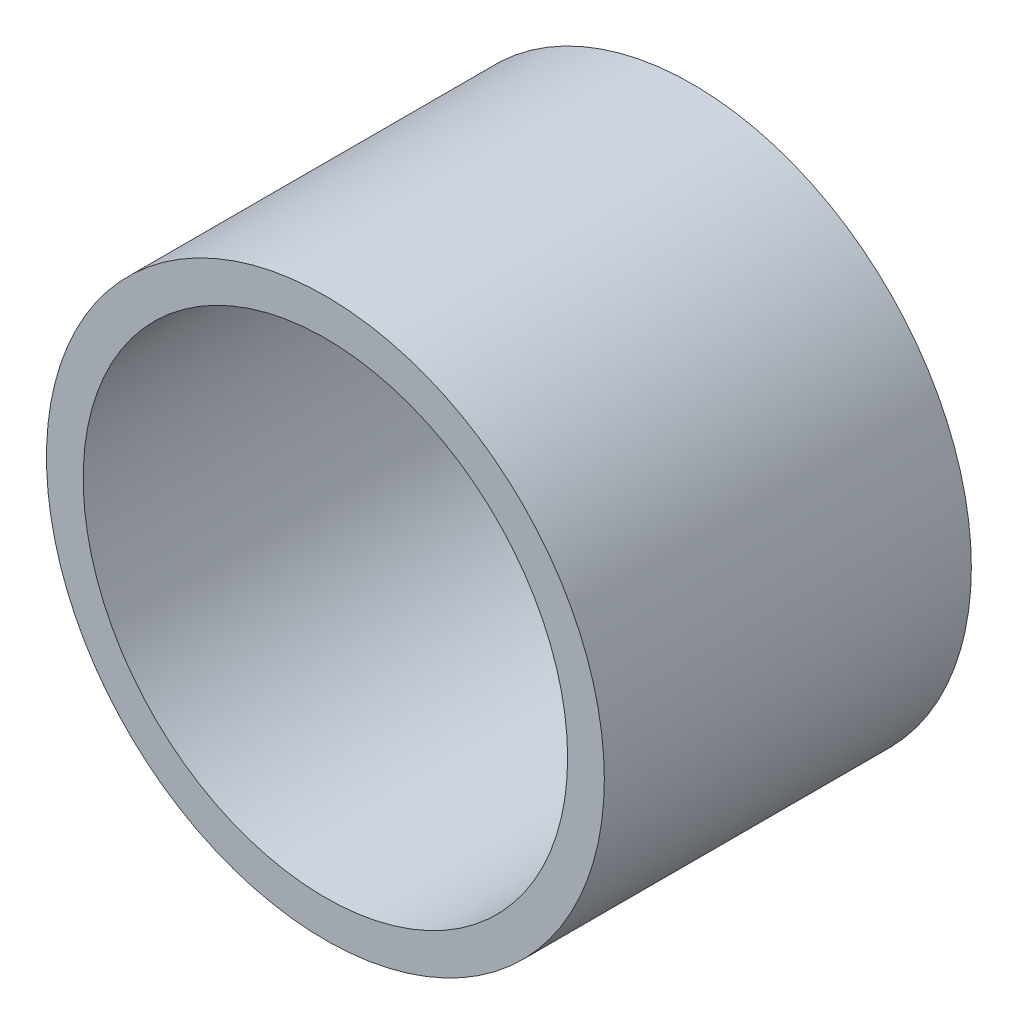
SolidWorks part; units mm, degrees
ref_plane "正面" through (0, 0, 0) normal (0, 0, 1) x (1, 0, 0)
ref_plane "平面" through (0, 0, 0) normal (0, 1, 0) x (1, 0, 0)
ref_plane "右側面" through (0, 0, 0) normal (1, 0, 0) x (0, 0, -1)
sketch "ｽｹｯﾁ1" plane through (0, 0, 0) normal (0, 0, 1) x (1, 0, 0)
  circle A0 centre (0, 0) radius 1.65
  circle A1 centre (0, 0) radius 1.9
  dimension "D1" = 3.3
  dimension "D2" = 3.8
extrude "ﾎﾞｽ - 押し出し1" add sketch "ｽｹｯﾁ1" along normal blind 2.5
